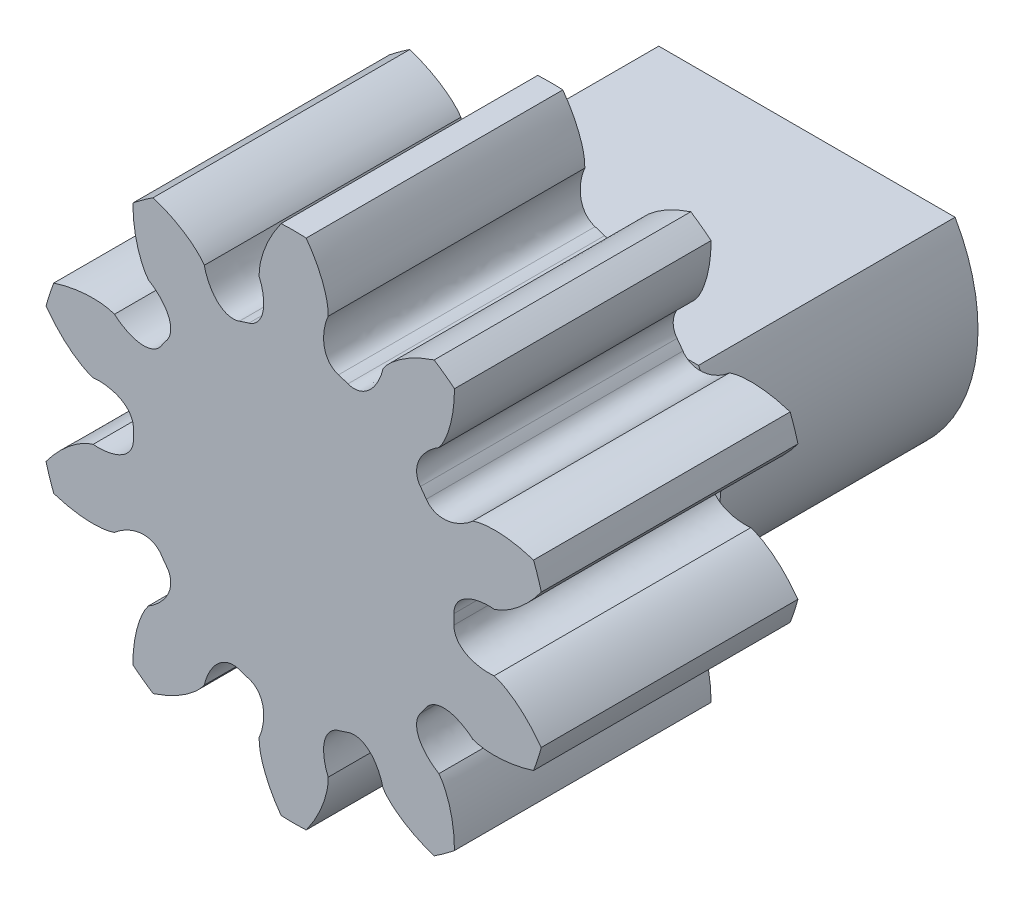
SolidWorks part; units mm, degrees
ref_plane "Спереди" through (0, 0, 0) normal (0, 0, 1) x (1, 0, 0)
ref_plane "Сверху" through (0, 0, 0) normal (0, 1, 0) x (1, 0, 0)
ref_plane "Справа" through (0, 0, 0) normal (1, 0, 0) x (0, 0, -1)
sketch "Sketch1" plane through (0, 0, 0) normal (0, 0, 1) x (1, 0, 0)
  line L6 (-3.3, 0) -> (3.3, 0) construction
  line L7 (0, -3.3) -> (0, 3.3) construction
  arc A90 (0.1469, 2.9964) -> (-0.1469, 2.9964) centre (0, 0) ccw
  arc A91 (-0.5237, 1.8004) -> (-0.6345, 1.7644) centre (0, 0) ccw
  arc A92 (-1.6424, 2.5105) -> (-1.8801, 2.3378) centre (0, 0) ccw
  arc A93 (-1.4819, 1.1487) -> (-1.5504, 1.0544) centre (0, 0) ccw
  arc A94 (-2.8044, 1.0656) -> (-2.8951, 0.7863) centre (0, 0) ccw
  arc A95 (-1.8741, 0.0583) -> (-1.8741, -0.0583) centre (0, 0) ccw
  arc A96 (-2.8951, -0.7863) -> (-2.8044, -1.0656) centre (0, 0) ccw
  arc A97 (-1.5504, -1.0544) -> (-1.4819, -1.1487) centre (0, 0) ccw
  arc A98 (-1.8801, -2.3378) -> (-1.6424, -2.5105) centre (0, 0) ccw
  arc A99 (-0.6345, -1.7644) -> (-0.5237, -1.8004) centre (0, 0) ccw
  arc A100 (-0.1469, -2.9964) -> (0.1469, -2.9964) centre (0, 0) ccw
  arc A101 (0.5237, -1.8004) -> (0.6345, -1.7644) centre (0, 0) ccw
  arc A102 (1.6424, -2.5105) -> (1.8801, -2.3378) centre (0, 0) ccw
  arc A103 (1.4819, -1.1487) -> (1.5504, -1.0544) centre (0, 0) ccw
  arc A104 (2.8044, -1.0656) -> (2.8951, -0.7863) centre (0, 0) ccw
  arc A105 (1.8741, -0.0583) -> (1.8741, 0.0583) centre (0, 0) ccw
  arc A106 (2.8951, 0.7863) -> (2.8044, 1.0656) centre (0, 0) ccw
  arc A107 (1.5504, 1.0544) -> (1.4819, 1.1487) centre (0, 0) ccw
  arc A108 (1.8801, 2.3378) -> (1.6424, 2.5105) centre (0, 0) ccw
  arc A109 (0.6345, 1.7644) -> (0.5237, 1.8004) centre (0, 0) ccw
  circle A110 centre (0, 0) radius 2.5 construction
  spline S176 degree 3 poles (0.4037, 2.3331) (0.3766, 2.2714) (0.3599, 2.2084) (0.3536, 2.144) (0.3502, 2.1088) (0.3485, 2.0724) (0.3525, 2.0372) (0.3552, 2.0138) (0.3594, 1.99) (0.3665, 1.9675) (0.3718, 1.9506) (0.3784, 1.9336) (0.3866, 1.9178) (0.3934, 1.9048) (0.4012, 1.892) (0.4101, 1.8803) (0.4179, 1.87) (0.4266, 1.8601) (0.4359, 1.8513) (0.4445, 1.8431) (0.4538, 1.8355) (0.4636, 1.8289) (0.4729, 1.8225) (0.4827, 1.8168) (0.4929, 1.812) (0.5028, 1.8074) (0.5131, 1.8035) (0.5237, 1.8004) knots 0 0 0 0 1 1 1 2 2 2 3 3 3 4 4 4 5 5 5 6 6 6 7 7 7 8 8 8 9 9 9 9
  spline S177 degree 3 poles (-0.4037, 2.3331) (-0.3766, 2.2714) (-0.3599, 2.2084) (-0.3536, 2.144) (-0.3502, 2.1088) (-0.3485, 2.0724) (-0.3525, 2.0372) (-0.3552, 2.0138) (-0.3594, 1.99) (-0.3665, 1.9675) (-0.3718, 1.9506) (-0.3784, 1.9336) (-0.3866, 1.9178) (-0.3934, 1.9048) (-0.4012, 1.892) (-0.4101, 1.8803) (-0.4179, 1.87) (-0.4266, 1.8601) (-0.4359, 1.8513) (-0.4445, 1.8431) (-0.4538, 1.8355) (-0.4636, 1.8289) (-0.4729, 1.8225) (-0.4827, 1.8168) (-0.4929, 1.812) (-0.5028, 1.8074) (-0.5131, 1.8035) (-0.5237, 1.8004) knots 0 0 0 0 1 1 1 2 2 2 3 3 3 4 4 4 5 5 5 6 6 6 7 7 7 8 8 8 9 9 9 9
  spline S178 degree 3 poles (0.4037, 2.3331) (0.4041, 2.3571) (0.4032, 2.381) (0.4009, 2.4048) (0.3985, 2.4293) (0.3942, 2.4537) (0.3894, 2.4778) (0.3844, 2.5026) (0.3781, 2.5273) (0.3711, 2.5516) (0.364, 2.5767) (0.3557, 2.6014) (0.3469, 2.6259) (0.3378, 2.6511) (0.3277, 2.6759) (0.3171, 2.7004) (0.3061, 2.7256) (0.2944, 2.7505) (0.282, 2.7749) (0.2693, 2.8001) (0.2559, 2.8248) (0.2419, 2.8492) (0.2275, 2.8743) (0.2124, 2.8989) (0.1968, 2.9231) (0.1808, 2.948) (0.1641, 2.9724) (0.1469, 2.9964) knots 0 0 0 0 1 1 1 2 2 2 3 3 3 4 4 4 5 5 5 6 6 6 7 7 7 8 8 8 9 9 9 9
  spline S179 degree 3 poles (-0.4037, 2.3331) (-0.4041, 2.3571) (-0.4032, 2.381) (-0.4009, 2.4048) (-0.3985, 2.4293) (-0.3942, 2.4537) (-0.3894, 2.4778) (-0.3844, 2.5026) (-0.3781, 2.5273) (-0.3711, 2.5516) (-0.364, 2.5767) (-0.3557, 2.6014) (-0.3469, 2.6259) (-0.3378, 2.6511) (-0.3277, 2.6759) (-0.3171, 2.7004) (-0.3061, 2.7256) (-0.2944, 2.7505) (-0.282, 2.7749) (-0.2693, 2.8001) (-0.2559, 2.8248) (-0.2419, 2.8492) (-0.2275, 2.8743) (-0.2124, 2.8989) (-0.1968, 2.9231) (-0.1808, 2.948) (-0.1641, 2.9724) (-0.1469, 2.9964) knots 0 0 0 0 1 1 1 2 2 2 3 3 3 4 4 4 5 5 5 6 6 6 7 7 7 8 8 8 9 9 9 9
  spline S180 degree 3 poles (-1.0448, 2.1248) (-1.0304, 2.059) (-1.0069, 1.9982) (-0.9741, 1.9424) (-0.9563, 1.9119) (-0.9362, 1.8814) (-0.9122, 1.8553) (-0.8963, 1.838) (-0.8789, 1.8212) (-0.86, 1.8072) (-0.8457, 1.7966) (-0.8304, 1.7867) (-0.8145, 1.7788) (-0.8013, 1.7722) (-0.7875, 1.7665) (-0.7734, 1.7622) (-0.7611, 1.7585) (-0.7483, 1.7556) (-0.7355, 1.7539) (-0.7238, 1.7524) (-0.7117, 1.7517) (-0.6999, 1.7521) (-0.6887, 1.7524) (-0.6774, 1.7536) (-0.6663, 1.7557) (-0.6556, 1.7577) (-0.645, 1.7606) (-0.6345, 1.7644) knots 0 0 0 0 1 1 1 2 2 2 3 3 3 4 4 4 5 5 5 6 6 6 7 7 7 8 8 8 9 9 9 9
  spline S181 degree 3 poles (-1.6979, 1.6502) (-1.6398, 1.6163) (-1.5893, 1.5751) (-1.5463, 1.5267) (-1.5228, 1.5003) (-1.5, 1.4718) (-1.4826, 1.4409) (-1.4711, 1.4204) (-1.4605, 1.3987) (-1.453, 1.3764) (-1.4473, 1.3595) (-1.4427, 1.3419) (-1.44, 1.3243) (-1.4379, 1.3097) (-1.4367, 1.2948) (-1.437, 1.2801) (-1.4373, 1.2672) (-1.4385, 1.2542) (-1.4408, 1.2415) (-1.443, 1.2299) (-1.446, 1.2182) (-1.45, 1.2071) (-1.4538, 1.1965) (-1.4585, 1.1861) (-1.4639, 1.1763) (-1.4691, 1.1667) (-1.4752, 1.1575) (-1.4819, 1.1487) knots 0 0 0 0 1 1 1 2 2 2 3 3 3 4 4 4 5 5 5 6 6 6 7 7 7 8 8 8 9 9 9 9
  spline S182 degree 3 poles (-1.0448, 2.1248) (-1.0585, 2.1445) (-1.0734, 2.1633) (-1.0892, 2.1811) (-1.1055, 2.1996) (-1.1233, 2.2168) (-1.1414, 2.2335) (-1.1601, 2.2506) (-1.1796, 2.2668) (-1.1996, 2.2825) (-1.2201, 2.2985) (-1.2413, 2.3137) (-1.2629, 2.3283) (-1.285, 2.3433) (-1.3077, 2.3575) (-1.3308, 2.3711) (-1.3544, 2.385) (-1.3785, 2.3982) (-1.4029, 2.4107) (-1.4279, 2.4236) (-1.4534, 2.4357) (-1.4791, 2.4473) (-1.5054, 2.459) (-1.5321, 2.4701) (-1.559, 2.4805) (-1.5865, 2.4912) (-1.6143, 2.5012) (-1.6424, 2.5105) knots 0 0 0 0 1 1 1 2 2 2 3 3 3 4 4 4 5 5 5 6 6 6 7 7 7 8 8 8 9 9 9 9
  spline S183 degree 3 poles (-1.6979, 1.6502) (-1.7124, 1.6694) (-1.7257, 1.6893) (-1.7378, 1.7099) (-1.7503, 1.7311) (-1.7612, 1.7534) (-1.7714, 1.7757) (-1.782, 1.7988) (-1.7914, 1.8224) (-1.8, 1.8462) (-1.809, 1.8706) (-1.8169, 1.8955) (-1.8241, 1.9205) (-1.8315, 1.9462) (-1.838, 1.9722) (-1.8438, 1.9983) (-1.8497, 2.0251) (-1.8548, 2.0521) (-1.8592, 2.0792) (-1.8637, 2.107) (-1.8674, 2.1349) (-1.8704, 2.1629) (-1.8735, 2.1916) (-1.8758, 2.2204) (-1.8774, 2.2492) (-1.879, 2.2787) (-1.8799, 2.3082) (-1.8801, 2.3378) knots 0 0 0 0 1 1 1 2 2 2 3 3 3 4 4 4 5 5 5 6 6 6 7 7 7 8 8 8 9 9 9 9
  spline S184 degree 3 poles (-2.0941, 1.1049) (-2.0439, 1.0601) (-1.9891, 1.0248) (-1.9298, 0.9988) (-1.8974, 0.9847) (-1.8633, 0.9718) (-1.8285, 0.9648) (-1.8054, 0.9601) (-1.7816, 0.9568) (-1.758, 0.9566) (-1.7402, 0.9564) (-1.722, 0.9574) (-1.7045, 0.9603) (-1.69, 0.9628) (-1.6754, 0.9663) (-1.6615, 0.9711) (-1.6493, 0.9753) (-1.6373, 0.9805) (-1.626, 0.9867) (-1.6156, 0.9923) (-1.6055, 0.9988) (-1.5961, 1.0061) (-1.5872, 1.0129) (-1.5787, 1.0206) (-1.571, 1.0287) (-1.5635, 1.0367) (-1.5567, 1.0453) (-1.5504, 1.0544) knots 0 0 0 0 1 1 1 2 2 2 3 3 3 4 4 4 5 5 5 6 6 6 7 7 7 8 8 8 9 9 9 9
  spline S185 degree 3 poles (-2.3436, 0.337) (-2.2767, 0.3437) (-2.2116, 0.3401) (-2.1484, 0.3262) (-2.1138, 0.3186) (-2.0786, 0.309) (-2.0464, 0.2942) (-2.025, 0.2844) (-2.0037, 0.2731) (-1.9845, 0.2595) (-1.97, 0.2491) (-1.9559, 0.2377) (-1.9434, 0.2249) (-1.9331, 0.2144) (-1.9234, 0.2031) (-1.915, 0.191) (-1.9076, 0.1804) (-1.9009, 0.1691) (-1.8954, 0.1575) (-1.8903, 0.1468) (-1.8859, 0.1356) (-1.8826, 0.1242) (-1.8795, 0.1135) (-1.8771, 0.1023) (-1.8757, 0.0912) (-1.8743, 0.0803) (-1.8738, 0.0693) (-1.8741, 0.0583) knots 0 0 0 0 1 1 1 2 2 2 3 3 3 4 4 4 5 5 5 6 6 6 7 7 7 8 8 8 9 9 9 9
  spline S186 degree 3 poles (-2.0941, 1.1049) (-2.1169, 1.1127) (-2.1399, 1.1192) (-2.1632, 1.1244) (-2.1872, 1.1297) (-2.2118, 1.1332) (-2.2362, 1.136) (-2.2614, 1.1389) (-2.2868, 1.1405) (-2.3121, 1.1414) (-2.3381, 1.1424) (-2.3642, 1.1422) (-2.3902, 1.1413) (-2.4169, 1.1405) (-2.4437, 1.1386) (-2.4703, 1.136) (-2.4976, 1.1334) (-2.5249, 1.1299) (-2.552, 1.1257) (-2.5798, 1.1214) (-2.6075, 1.1163) (-2.6351, 1.1105) (-2.6633, 1.1046) (-2.6914, 1.0978) (-2.7193, 1.0904) (-2.7478, 1.0829) (-2.7762, 1.0746) (-2.8044, 1.0656) knots 0 0 0 0 1 1 1 2 2 2 3 3 3 4 4 4 5 5 5 6 6 6 7 7 7 8 8 8 9 9 9 9
  spline S187 degree 3 poles (-2.3436, 0.337) (-2.3666, 0.3441) (-2.3891, 0.3523) (-2.411, 0.3619) (-2.4335, 0.3717) (-2.4554, 0.3833) (-2.4769, 0.3954) (-2.4989, 0.4078) (-2.5204, 0.4214) (-2.5414, 0.4356) (-2.563, 0.4501) (-2.5841, 0.4656) (-2.6046, 0.4816) (-2.6257, 0.498) (-2.6462, 0.5152) (-2.6663, 0.5329) (-2.6868, 0.5511) (-2.7068, 0.57) (-2.7263, 0.5893) (-2.7463, 0.6091) (-2.7657, 0.6296) (-2.7845, 0.6504) (-2.8039, 0.6718) (-2.8226, 0.6938) (-2.8409, 0.7161) (-2.8595, 0.739) (-2.8776, 0.7624) (-2.8951, 0.7863) knots 0 0 0 0 1 1 1 2 2 2 3 3 3 4 4 4 5 5 5 6 6 6 7 7 7 8 8 8 9 9 9 9
  spline S188 degree 3 poles (-2.3436, -0.337) (-2.2767, -0.3437) (-2.2116, -0.3401) (-2.1484, -0.3262) (-2.1138, -0.3186) (-2.0786, -0.309) (-2.0464, -0.2942) (-2.025, -0.2844) (-2.0037, -0.2731) (-1.9845, -0.2595) (-1.97, -0.2491) (-1.9559, -0.2377) (-1.9434, -0.2249) (-1.9331, -0.2144) (-1.9234, -0.2031) (-1.915, -0.191) (-1.9076, -0.1804) (-1.9009, -0.1691) (-1.8954, -0.1575) (-1.8903, -0.1468) (-1.8859, -0.1356) (-1.8826, -0.1242) (-1.8795, -0.1135) (-1.8771, -0.1023) (-1.8757, -0.0912) (-1.8743, -0.0803) (-1.8738, -0.0693) (-1.8741, -0.0583) knots 0 0 0 0 1 1 1 2 2 2 3 3 3 4 4 4 5 5 5 6 6 6 7 7 7 8 8 8 9 9 9 9
  spline S189 degree 3 poles (-2.0941, -1.1049) (-2.0439, -1.0601) (-1.9891, -1.0248) (-1.9298, -0.9988) (-1.8974, -0.9847) (-1.8633, -0.9718) (-1.8285, -0.9648) (-1.8054, -0.9601) (-1.7816, -0.9568) (-1.758, -0.9566) (-1.7402, -0.9564) (-1.722, -0.9574) (-1.7045, -0.9603) (-1.69, -0.9628) (-1.6754, -0.9663) (-1.6615, -0.9711) (-1.6493, -0.9753) (-1.6373, -0.9805) (-1.626, -0.9867) (-1.6156, -0.9923) (-1.6055, -0.9988) (-1.5961, -1.0061) (-1.5872, -1.0129) (-1.5787, -1.0206) (-1.571, -1.0287) (-1.5635, -1.0367) (-1.5567, -1.0453) (-1.5504, -1.0544) knots 0 0 0 0 1 1 1 2 2 2 3 3 3 4 4 4 5 5 5 6 6 6 7 7 7 8 8 8 9 9 9 9
  spline S190 degree 3 poles (-2.3436, -0.337) (-2.3666, -0.3441) (-2.3891, -0.3523) (-2.411, -0.3619) (-2.4335, -0.3717) (-2.4554, -0.3833) (-2.4769, -0.3954) (-2.4989, -0.4078) (-2.5204, -0.4214) (-2.5414, -0.4356) (-2.563, -0.4501) (-2.5841, -0.4656) (-2.6046, -0.4816) (-2.6257, -0.498) (-2.6462, -0.5152) (-2.6663, -0.5329) (-2.6868, -0.5511) (-2.7068, -0.57) (-2.7263, -0.5893) (-2.7463, -0.6091) (-2.7657, -0.6296) (-2.7845, -0.6504) (-2.8039, -0.6718) (-2.8226, -0.6938) (-2.8409, -0.7161) (-2.8595, -0.739) (-2.8776, -0.7624) (-2.8951, -0.7863) knots 0 0 0 0 1 1 1 2 2 2 3 3 3 4 4 4 5 5 5 6 6 6 7 7 7 8 8 8 9 9 9 9
  spline S191 degree 3 poles (-2.0941, -1.1049) (-2.1169, -1.1127) (-2.1399, -1.1192) (-2.1632, -1.1244) (-2.1872, -1.1297) (-2.2118, -1.1332) (-2.2362, -1.136) (-2.2614, -1.1389) (-2.2868, -1.1405) (-2.3121, -1.1414) (-2.3381, -1.1424) (-2.3642, -1.1422) (-2.3902, -1.1413) (-2.4169, -1.1405) (-2.4437, -1.1386) (-2.4703, -1.136) (-2.4976, -1.1334) (-2.5249, -1.1299) (-2.552, -1.1257) (-2.5798, -1.1214) (-2.6075, -1.1163) (-2.6351, -1.1105) (-2.6633, -1.1046) (-2.6914, -1.0978) (-2.7193, -1.0904) (-2.7478, -1.0829) (-2.7762, -1.0746) (-2.8044, -1.0656) knots 0 0 0 0 1 1 1 2 2 2 3 3 3 4 4 4 5 5 5 6 6 6 7 7 7 8 8 8 9 9 9 9
  spline S192 degree 3 poles (-1.6979, -1.6502) (-1.6398, -1.6163) (-1.5893, -1.5751) (-1.5463, -1.5267) (-1.5228, -1.5003) (-1.5, -1.4718) (-1.4826, -1.4409) (-1.4711, -1.4204) (-1.4605, -1.3987) (-1.453, -1.3764) (-1.4473, -1.3595) (-1.4427, -1.3419) (-1.44, -1.3243) (-1.4379, -1.3097) (-1.4367, -1.2948) (-1.437, -1.2801) (-1.4373, -1.2672) (-1.4385, -1.2542) (-1.4408, -1.2415) (-1.443, -1.2299) (-1.446, -1.2182) (-1.45, -1.2071) (-1.4538, -1.1965) (-1.4585, -1.1861) (-1.4639, -1.1763) (-1.4691, -1.1667) (-1.4752, -1.1575) (-1.4819, -1.1487) knots 0 0 0 0 1 1 1 2 2 2 3 3 3 4 4 4 5 5 5 6 6 6 7 7 7 8 8 8 9 9 9 9
  spline S193 degree 3 poles (-1.0448, -2.1248) (-1.0304, -2.059) (-1.0069, -1.9982) (-0.9741, -1.9424) (-0.9563, -1.9119) (-0.9362, -1.8814) (-0.9122, -1.8553) (-0.8963, -1.838) (-0.8789, -1.8212) (-0.86, -1.8072) (-0.8457, -1.7966) (-0.8304, -1.7867) (-0.8145, -1.7788) (-0.8013, -1.7722) (-0.7875, -1.7665) (-0.7734, -1.7622) (-0.7611, -1.7585) (-0.7483, -1.7556) (-0.7355, -1.7539) (-0.7238, -1.7524) (-0.7117, -1.7517) (-0.6999, -1.7521) (-0.6887, -1.7524) (-0.6774, -1.7536) (-0.6663, -1.7557) (-0.6556, -1.7577) (-0.645, -1.7606) (-0.6345, -1.7644) knots 0 0 0 0 1 1 1 2 2 2 3 3 3 4 4 4 5 5 5 6 6 6 7 7 7 8 8 8 9 9 9 9
  spline S194 degree 3 poles (-1.6979, -1.6502) (-1.7124, -1.6694) (-1.7257, -1.6893) (-1.7378, -1.7099) (-1.7503, -1.7311) (-1.7612, -1.7534) (-1.7714, -1.7757) (-1.782, -1.7988) (-1.7914, -1.8224) (-1.8, -1.8462) (-1.809, -1.8706) (-1.8169, -1.8955) (-1.8241, -1.9205) (-1.8315, -1.9462) (-1.838, -1.9722) (-1.8438, -1.9983) (-1.8497, -2.0251) (-1.8548, -2.0521) (-1.8592, -2.0792) (-1.8637, -2.107) (-1.8674, -2.1349) (-1.8704, -2.1629) (-1.8735, -2.1916) (-1.8758, -2.2204) (-1.8774, -2.2492) (-1.879, -2.2787) (-1.8799, -2.3082) (-1.8801, -2.3378) knots 0 0 0 0 1 1 1 2 2 2 3 3 3 4 4 4 5 5 5 6 6 6 7 7 7 8 8 8 9 9 9 9
  spline S195 degree 3 poles (-1.0448, -2.1248) (-1.0585, -2.1445) (-1.0734, -2.1633) (-1.0892, -2.1811) (-1.1055, -2.1996) (-1.1233, -2.2168) (-1.1414, -2.2335) (-1.1601, -2.2506) (-1.1796, -2.2668) (-1.1996, -2.2825) (-1.2201, -2.2985) (-1.2413, -2.3137) (-1.2629, -2.3283) (-1.285, -2.3433) (-1.3077, -2.3575) (-1.3308, -2.3711) (-1.3544, -2.385) (-1.3785, -2.3982) (-1.4029, -2.4107) (-1.4279, -2.4236) (-1.4534, -2.4357) (-1.4791, -2.4473) (-1.5054, -2.459) (-1.5321, -2.4701) (-1.559, -2.4805) (-1.5865, -2.4912) (-1.6143, -2.5012) (-1.6424, -2.5105) knots 0 0 0 0 1 1 1 2 2 2 3 3 3 4 4 4 5 5 5 6 6 6 7 7 7 8 8 8 9 9 9 9
  spline S196 degree 3 poles (-0.4037, -2.3331) (-0.3766, -2.2714) (-0.3599, -2.2084) (-0.3536, -2.144) (-0.3502, -2.1088) (-0.3485, -2.0724) (-0.3525, -2.0372) (-0.3552, -2.0138) (-0.3594, -1.99) (-0.3665, -1.9675) (-0.3718, -1.9506) (-0.3784, -1.9336) (-0.3866, -1.9178) (-0.3934, -1.9048) (-0.4012, -1.892) (-0.4101, -1.8803) (-0.4179, -1.87) (-0.4266, -1.8601) (-0.4359, -1.8513) (-0.4445, -1.8431) (-0.4538, -1.8355) (-0.4636, -1.8289) (-0.4729, -1.8225) (-0.4827, -1.8168) (-0.4929, -1.812) (-0.5028, -1.8074) (-0.5131, -1.8035) (-0.5237, -1.8004) knots 0 0 0 0 1 1 1 2 2 2 3 3 3 4 4 4 5 5 5 6 6 6 7 7 7 8 8 8 9 9 9 9
  spline S197 degree 3 poles (0.4037, -2.3331) (0.3766, -2.2714) (0.3599, -2.2084) (0.3536, -2.144) (0.3502, -2.1088) (0.3485, -2.0724) (0.3525, -2.0372) (0.3552, -2.0138) (0.3594, -1.99) (0.3665, -1.9675) (0.3718, -1.9506) (0.3784, -1.9336) (0.3866, -1.9178) (0.3934, -1.9048) (0.4012, -1.892) (0.4101, -1.8803) (0.4179, -1.87) (0.4266, -1.8601) (0.4359, -1.8513) (0.4445, -1.8431) (0.4538, -1.8355) (0.4636, -1.8289) (0.4729, -1.8225) (0.4827, -1.8168) (0.4929, -1.812) (0.5028, -1.8074) (0.5131, -1.8035) (0.5237, -1.8004) knots 0 0 0 0 1 1 1 2 2 2 3 3 3 4 4 4 5 5 5 6 6 6 7 7 7 8 8 8 9 9 9 9
  spline S198 degree 3 poles (-0.4037, -2.3331) (-0.4041, -2.3571) (-0.4032, -2.381) (-0.4009, -2.4048) (-0.3985, -2.4293) (-0.3942, -2.4537) (-0.3894, -2.4778) (-0.3844, -2.5026) (-0.3781, -2.5273) (-0.3711, -2.5516) (-0.364, -2.5767) (-0.3557, -2.6014) (-0.3469, -2.6259) (-0.3378, -2.6511) (-0.3277, -2.6759) (-0.3171, -2.7004) (-0.3061, -2.7256) (-0.2944, -2.7505) (-0.282, -2.7749) (-0.2693, -2.8001) (-0.2559, -2.8248) (-0.2419, -2.8492) (-0.2275, -2.8743) (-0.2124, -2.8989) (-0.1968, -2.9231) (-0.1808, -2.948) (-0.1641, -2.9724) (-0.1469, -2.9964) knots 0 0 0 0 1 1 1 2 2 2 3 3 3 4 4 4 5 5 5 6 6 6 7 7 7 8 8 8 9 9 9 9
  spline S199 degree 3 poles (0.4037, -2.3331) (0.4041, -2.3571) (0.4032, -2.381) (0.4009, -2.4048) (0.3985, -2.4293) (0.3942, -2.4537) (0.3894, -2.4778) (0.3844, -2.5026) (0.3781, -2.5273) (0.3711, -2.5516) (0.364, -2.5767) (0.3557, -2.6014) (0.3469, -2.6259) (0.3378, -2.6511) (0.3277, -2.6759) (0.3171, -2.7004) (0.3061, -2.7256) (0.2944, -2.7505) (0.282, -2.7749) (0.2693, -2.8001) (0.2559, -2.8248) (0.2419, -2.8492) (0.2275, -2.8743) (0.2124, -2.8989) (0.1968, -2.9231) (0.1808, -2.948) (0.1641, -2.9724) (0.1469, -2.9964) knots 0 0 0 0 1 1 1 2 2 2 3 3 3 4 4 4 5 5 5 6 6 6 7 7 7 8 8 8 9 9 9 9
  spline S200 degree 3 poles (1.0448, -2.1248) (1.0304, -2.059) (1.0069, -1.9982) (0.9741, -1.9424) (0.9563, -1.9119) (0.9362, -1.8814) (0.9122, -1.8553) (0.8963, -1.838) (0.8789, -1.8212) (0.86, -1.8072) (0.8457, -1.7966) (0.8304, -1.7867) (0.8145, -1.7788) (0.8013, -1.7722) (0.7875, -1.7665) (0.7734, -1.7622) (0.7611, -1.7585) (0.7483, -1.7556) (0.7355, -1.7539) (0.7238, -1.7524) (0.7117, -1.7517) (0.6999, -1.7521) (0.6887, -1.7524) (0.6774, -1.7536) (0.6663, -1.7557) (0.6556, -1.7577) (0.645, -1.7606) (0.6345, -1.7644) knots 0 0 0 0 1 1 1 2 2 2 3 3 3 4 4 4 5 5 5 6 6 6 7 7 7 8 8 8 9 9 9 9
  spline S201 degree 3 poles (1.6979, -1.6502) (1.6398, -1.6163) (1.5893, -1.5751) (1.5463, -1.5267) (1.5228, -1.5003) (1.5, -1.4718) (1.4826, -1.4409) (1.4711, -1.4204) (1.4605, -1.3987) (1.453, -1.3764) (1.4473, -1.3595) (1.4427, -1.3419) (1.44, -1.3243) (1.4379, -1.3097) (1.4367, -1.2948) (1.437, -1.2801) (1.4373, -1.2672) (1.4385, -1.2542) (1.4408, -1.2415) (1.443, -1.2299) (1.446, -1.2182) (1.45, -1.2071) (1.4538, -1.1965) (1.4585, -1.1861) (1.4639, -1.1763) (1.4691, -1.1667) (1.4752, -1.1575) (1.4819, -1.1487) knots 0 0 0 0 1 1 1 2 2 2 3 3 3 4 4 4 5 5 5 6 6 6 7 7 7 8 8 8 9 9 9 9
  spline S202 degree 3 poles (1.0448, -2.1248) (1.0585, -2.1445) (1.0734, -2.1633) (1.0892, -2.1811) (1.1055, -2.1996) (1.1233, -2.2168) (1.1414, -2.2335) (1.1601, -2.2506) (1.1796, -2.2668) (1.1996, -2.2825) (1.2201, -2.2985) (1.2413, -2.3137) (1.2629, -2.3283) (1.285, -2.3433) (1.3077, -2.3575) (1.3308, -2.3711) (1.3544, -2.385) (1.3785, -2.3982) (1.4029, -2.4107) (1.4279, -2.4236) (1.4534, -2.4357) (1.4791, -2.4473) (1.5054, -2.459) (1.5321, -2.4701) (1.559, -2.4805) (1.5865, -2.4912) (1.6143, -2.5012) (1.6424, -2.5105) knots 0 0 0 0 1 1 1 2 2 2 3 3 3 4 4 4 5 5 5 6 6 6 7 7 7 8 8 8 9 9 9 9
  spline S203 degree 3 poles (1.6979, -1.6502) (1.7124, -1.6694) (1.7257, -1.6893) (1.7378, -1.7099) (1.7503, -1.7311) (1.7612, -1.7534) (1.7714, -1.7757) (1.782, -1.7988) (1.7914, -1.8224) (1.8, -1.8462) (1.809, -1.8706) (1.8169, -1.8955) (1.8241, -1.9205) (1.8315, -1.9462) (1.838, -1.9722) (1.8438, -1.9983) (1.8497, -2.0251) (1.8548, -2.0521) (1.8592, -2.0792) (1.8637, -2.107) (1.8674, -2.1349) (1.8704, -2.1629) (1.8735, -2.1916) (1.8758, -2.2204) (1.8774, -2.2492) (1.879, -2.2787) (1.8799, -2.3082) (1.8801, -2.3378) knots 0 0 0 0 1 1 1 2 2 2 3 3 3 4 4 4 5 5 5 6 6 6 7 7 7 8 8 8 9 9 9 9
  spline S204 degree 3 poles (2.0941, -1.1049) (2.0439, -1.0601) (1.9891, -1.0248) (1.9298, -0.9988) (1.8974, -0.9847) (1.8633, -0.9718) (1.8285, -0.9648) (1.8054, -0.9601) (1.7816, -0.9568) (1.758, -0.9566) (1.7402, -0.9564) (1.722, -0.9574) (1.7045, -0.9603) (1.69, -0.9628) (1.6754, -0.9663) (1.6615, -0.9711) (1.6493, -0.9753) (1.6373, -0.9805) (1.626, -0.9867) (1.6156, -0.9923) (1.6055, -0.9988) (1.5961, -1.0061) (1.5872, -1.0129) (1.5787, -1.0206) (1.571, -1.0287) (1.5635, -1.0367) (1.5567, -1.0453) (1.5504, -1.0544) knots 0 0 0 0 1 1 1 2 2 2 3 3 3 4 4 4 5 5 5 6 6 6 7 7 7 8 8 8 9 9 9 9
  spline S205 degree 3 poles (2.3436, -0.337) (2.2767, -0.3437) (2.2116, -0.3401) (2.1484, -0.3262) (2.1138, -0.3186) (2.0786, -0.309) (2.0464, -0.2942) (2.025, -0.2844) (2.0037, -0.2731) (1.9845, -0.2595) (1.97, -0.2491) (1.9559, -0.2377) (1.9434, -0.2249) (1.9331, -0.2144) (1.9234, -0.2031) (1.915, -0.191) (1.9076, -0.1804) (1.9009, -0.1691) (1.8954, -0.1575) (1.8903, -0.1468) (1.8859, -0.1356) (1.8826, -0.1242) (1.8795, -0.1135) (1.8771, -0.1023) (1.8757, -0.0912) (1.8743, -0.0803) (1.8738, -0.0693) (1.8741, -0.0583) knots 0 0 0 0 1 1 1 2 2 2 3 3 3 4 4 4 5 5 5 6 6 6 7 7 7 8 8 8 9 9 9 9
  spline S206 degree 3 poles (2.0941, -1.1049) (2.1169, -1.1127) (2.1399, -1.1192) (2.1632, -1.1244) (2.1872, -1.1297) (2.2118, -1.1332) (2.2362, -1.136) (2.2614, -1.1389) (2.2868, -1.1405) (2.3121, -1.1414) (2.3381, -1.1424) (2.3642, -1.1422) (2.3902, -1.1413) (2.4169, -1.1405) (2.4437, -1.1386) (2.4703, -1.136) (2.4976, -1.1334) (2.5249, -1.1299) (2.552, -1.1257) (2.5798, -1.1214) (2.6075, -1.1163) (2.6351, -1.1105) (2.6633, -1.1046) (2.6914, -1.0978) (2.7193, -1.0904) (2.7478, -1.0829) (2.7762, -1.0746) (2.8044, -1.0656) knots 0 0 0 0 1 1 1 2 2 2 3 3 3 4 4 4 5 5 5 6 6 6 7 7 7 8 8 8 9 9 9 9
  spline S207 degree 3 poles (2.3436, -0.337) (2.3666, -0.3441) (2.3891, -0.3523) (2.411, -0.3619) (2.4335, -0.3717) (2.4554, -0.3833) (2.4769, -0.3954) (2.4989, -0.4078) (2.5204, -0.4214) (2.5414, -0.4356) (2.563, -0.4501) (2.5841, -0.4656) (2.6046, -0.4816) (2.6257, -0.498) (2.6462, -0.5152) (2.6663, -0.5329) (2.6868, -0.5511) (2.7068, -0.57) (2.7263, -0.5893) (2.7463, -0.6091) (2.7657, -0.6296) (2.7845, -0.6504) (2.8039, -0.6718) (2.8226, -0.6938) (2.8409, -0.7161) (2.8595, -0.739) (2.8776, -0.7624) (2.8951, -0.7863) knots 0 0 0 0 1 1 1 2 2 2 3 3 3 4 4 4 5 5 5 6 6 6 7 7 7 8 8 8 9 9 9 9
  spline S208 degree 3 poles (2.3436, 0.337) (2.2767, 0.3437) (2.2116, 0.3401) (2.1484, 0.3262) (2.1138, 0.3186) (2.0786, 0.309) (2.0464, 0.2942) (2.025, 0.2844) (2.0037, 0.2731) (1.9845, 0.2595) (1.97, 0.2491) (1.9559, 0.2377) (1.9434, 0.2249) (1.9331, 0.2144) (1.9234, 0.2031) (1.915, 0.191) (1.9076, 0.1804) (1.9009, 0.1691) (1.8954, 0.1575) (1.8903, 0.1468) (1.8859, 0.1356) (1.8826, 0.1242) (1.8795, 0.1135) (1.8771, 0.1023) (1.8757, 0.0912) (1.8743, 0.0803) (1.8738, 0.0693) (1.8741, 0.0583) knots 0 0 0 0 1 1 1 2 2 2 3 3 3 4 4 4 5 5 5 6 6 6 7 7 7 8 8 8 9 9 9 9
  spline S209 degree 3 poles (2.0941, 1.1049) (2.0439, 1.0601) (1.9891, 1.0248) (1.9298, 0.9988) (1.8974, 0.9847) (1.8633, 0.9718) (1.8285, 0.9648) (1.8054, 0.9601) (1.7816, 0.9568) (1.758, 0.9566) (1.7402, 0.9564) (1.722, 0.9574) (1.7045, 0.9603) (1.69, 0.9628) (1.6754, 0.9663) (1.6615, 0.9711) (1.6493, 0.9753) (1.6373, 0.9805) (1.626, 0.9867) (1.6156, 0.9923) (1.6055, 0.9988) (1.5961, 1.0061) (1.5872, 1.0129) (1.5787, 1.0206) (1.571, 1.0287) (1.5635, 1.0367) (1.5567, 1.0453) (1.5504, 1.0544) knots 0 0 0 0 1 1 1 2 2 2 3 3 3 4 4 4 5 5 5 6 6 6 7 7 7 8 8 8 9 9 9 9
  spline S210 degree 3 poles (2.3436, 0.337) (2.3666, 0.3441) (2.3891, 0.3523) (2.411, 0.3619) (2.4335, 0.3717) (2.4554, 0.3833) (2.4769, 0.3954) (2.4989, 0.4078) (2.5204, 0.4214) (2.5414, 0.4356) (2.563, 0.4501) (2.5841, 0.4656) (2.6046, 0.4816) (2.6257, 0.498) (2.6462, 0.5152) (2.6663, 0.5329) (2.6868, 0.5511) (2.7068, 0.57) (2.7263, 0.5893) (2.7463, 0.6091) (2.7657, 0.6296) (2.7845, 0.6504) (2.8039, 0.6718) (2.8226, 0.6938) (2.8409, 0.7161) (2.8595, 0.739) (2.8776, 0.7624) (2.8951, 0.7863) knots 0 0 0 0 1 1 1 2 2 2 3 3 3 4 4 4 5 5 5 6 6 6 7 7 7 8 8 8 9 9 9 9
  spline S211 degree 3 poles (2.0941, 1.1049) (2.1169, 1.1127) (2.1399, 1.1192) (2.1632, 1.1244) (2.1872, 1.1297) (2.2118, 1.1332) (2.2362, 1.136) (2.2614, 1.1389) (2.2868, 1.1405) (2.3121, 1.1414) (2.3381, 1.1424) (2.3642, 1.1422) (2.3902, 1.1413) (2.4169, 1.1405) (2.4437, 1.1386) (2.4703, 1.136) (2.4976, 1.1334) (2.5249, 1.1299) (2.552, 1.1257) (2.5798, 1.1214) (2.6075, 1.1163) (2.6351, 1.1105) (2.6633, 1.1046) (2.6914, 1.0978) (2.7193, 1.0904) (2.7478, 1.0829) (2.7762, 1.0746) (2.8044, 1.0656) knots 0 0 0 0 1 1 1 2 2 2 3 3 3 4 4 4 5 5 5 6 6 6 7 7 7 8 8 8 9 9 9 9
  spline S212 degree 3 poles (1.6979, 1.6502) (1.6398, 1.6163) (1.5893, 1.5751) (1.5463, 1.5267) (1.5228, 1.5003) (1.5, 1.4718) (1.4826, 1.4409) (1.4711, 1.4204) (1.4605, 1.3987) (1.453, 1.3764) (1.4473, 1.3595) (1.4427, 1.3419) (1.44, 1.3243) (1.4379, 1.3097) (1.4367, 1.2948) (1.437, 1.2801) (1.4373, 1.2672) (1.4385, 1.2542) (1.4408, 1.2415) (1.443, 1.2299) (1.446, 1.2182) (1.45, 1.2071) (1.4538, 1.1965) (1.4585, 1.1861) (1.4639, 1.1763) (1.4691, 1.1667) (1.4752, 1.1575) (1.4819, 1.1487) knots 0 0 0 0 1 1 1 2 2 2 3 3 3 4 4 4 5 5 5 6 6 6 7 7 7 8 8 8 9 9 9 9
  spline S213 degree 3 poles (1.0448, 2.1248) (1.0304, 2.059) (1.0069, 1.9982) (0.9741, 1.9424) (0.9563, 1.9119) (0.9362, 1.8814) (0.9122, 1.8553) (0.8963, 1.838) (0.8789, 1.8212) (0.86, 1.8072) (0.8457, 1.7966) (0.8304, 1.7867) (0.8145, 1.7788) (0.8013, 1.7722) (0.7875, 1.7665) (0.7734, 1.7622) (0.7611, 1.7585) (0.7483, 1.7556) (0.7355, 1.7539) (0.7238, 1.7524) (0.7117, 1.7517) (0.6999, 1.7521) (0.6887, 1.7524) (0.6774, 1.7536) (0.6663, 1.7557) (0.6556, 1.7577) (0.645, 1.7606) (0.6345, 1.7644) knots 0 0 0 0 1 1 1 2 2 2 3 3 3 4 4 4 5 5 5 6 6 6 7 7 7 8 8 8 9 9 9 9
  spline S214 degree 3 poles (1.6979, 1.6502) (1.7124, 1.6694) (1.7257, 1.6893) (1.7378, 1.7099) (1.7503, 1.7311) (1.7612, 1.7534) (1.7714, 1.7757) (1.782, 1.7988) (1.7914, 1.8224) (1.8, 1.8462) (1.809, 1.8706) (1.8169, 1.8955) (1.8241, 1.9205) (1.8315, 1.9462) (1.838, 1.9722) (1.8438, 1.9983) (1.8497, 2.0251) (1.8548, 2.0521) (1.8592, 2.0792) (1.8637, 2.107) (1.8674, 2.1349) (1.8704, 2.1629) (1.8735, 2.1916) (1.8758, 2.2204) (1.8774, 2.2492) (1.879, 2.2787) (1.8799, 2.3082) (1.8801, 2.3378) knots 0 0 0 0 1 1 1 2 2 2 3 3 3 4 4 4 5 5 5 6 6 6 7 7 7 8 8 8 9 9 9 9
  spline S215 degree 3 poles (1.0448, 2.1248) (1.0585, 2.1445) (1.0734, 2.1633) (1.0892, 2.1811) (1.1055, 2.1996) (1.1233, 2.2168) (1.1414, 2.2335) (1.1601, 2.2506) (1.1796, 2.2668) (1.1996, 2.2825) (1.2201, 2.2985) (1.2413, 2.3137) (1.2629, 2.3283) (1.285, 2.3433) (1.3077, 2.3575) (1.3308, 2.3711) (1.3544, 2.385) (1.3785, 2.3982) (1.4029, 2.4107) (1.4279, 2.4236) (1.4534, 2.4357) (1.4791, 2.4473) (1.5054, 2.459) (1.5321, 2.4701) (1.559, 2.4805) (1.5865, 2.4912) (1.6143, 2.5012) (1.6424, 2.5105) knots 0 0 0 0 1 1 1 2 2 2 3 3 3 4 4 4 5 5 5 6 6 6 7 7 7 8 8 8 9 9 9 9
extrude "Extrude1" add sketch "Sketch1" along normal blind 3
sketch "Sketch2" plane through (0, 0, 0) normal (0, 0, -1) x (-1, 0, 0)
  line L0 (0, -2) -> (0, 1)
  line L1 (0, 1) -> (-1.7321, 1)
  line L2 (0, 1) -> (1.7321, 1)
  arc A0 (-1.7321, 1) -> (1.7321, 1) centre (0, 0) ccw
extrude "Extrude2" add sketch "Sketch2" along normal blind 3 contours L1 A0 L0 | L0 A0 L2
